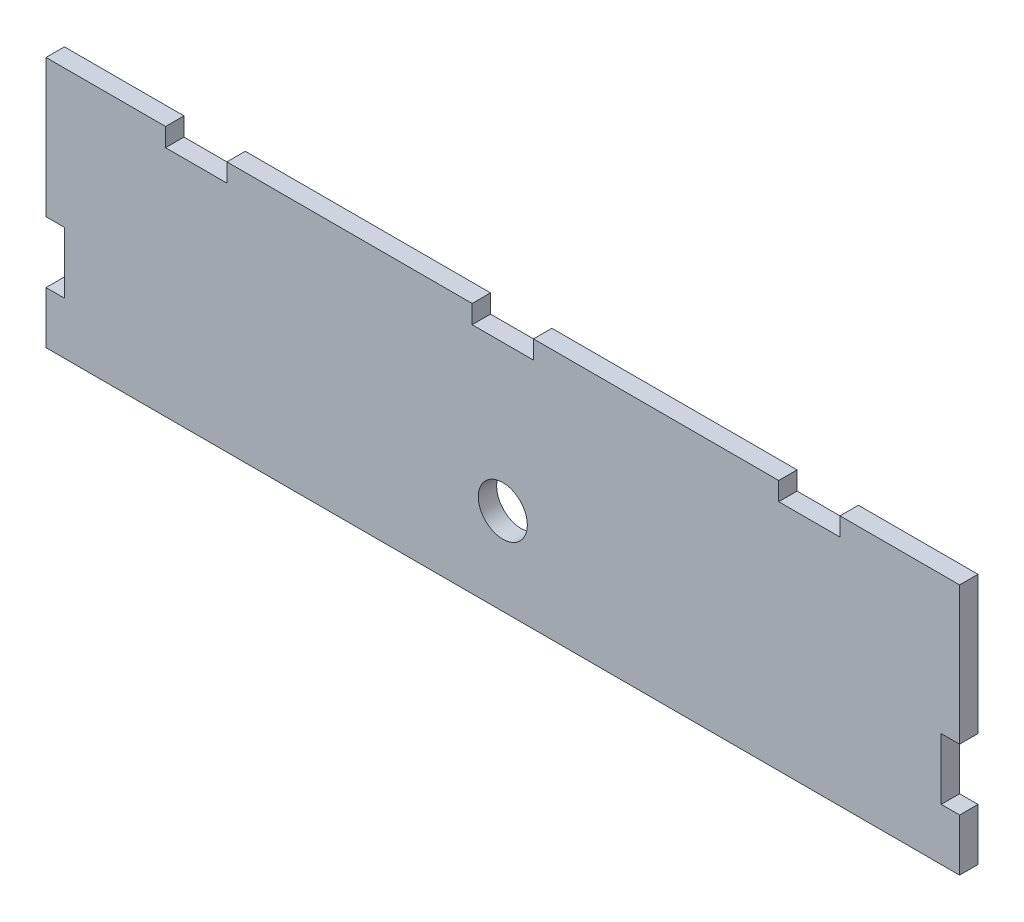
SolidWorks part; units mm, degrees
ref_plane "Front Plane" through (0, 0, 0) normal (0, 0, 1) x (1, 0, 0)
ref_plane "Top Plane" through (0, 0, 0) normal (0, 1, 0) x (1, 0, 0)
ref_plane "Right Plane" through (0, 0, 0) normal (1, 0, 0) x (0, 0, -1)
sketch "Sketch1" plane through (0, 0, 0) normal (0, 0, 1) x (1, 0, 0)
  line L2 (-74.5, 14) -> (-74.5, -8.5)
  line L3 (-74.5, -27) -> (74.5, -27)
  line L4 (74.5, 14) -> (74.5, -8.5)
  line L7 (-5, 14) -> (-5, 11)
  line L8 (-5, 11) -> (5, 11)
  line L9 (5, 14) -> (5, 11)
  line L11 (45, 14) -> (45, 11)
  line L12 (45, 11) -> (55, 11)
  line L13 (55, 14) -> (55, 11)
  line L27 (71.5, -8.5) -> (74.5, -8.5)
  line L28 (71.5, -8.5) -> (71.5, -18.5)
  line L29 (71.5, -18.5) -> (74.5, -18.5)
  line L31 (-71.5, -18.5) -> (-74.5, -18.5)
  line L32 (-71.5, -8.5) -> (-71.5, -18.5)
  line L33 (-71.5, -8.5) -> (-74.5, -8.5)
  line L34 (-74.5, -18.5) -> (-74.5, -27)
  line L35 (74.5, -18.5) -> (74.5, -27)
  line L37 (-55, 14) -> (-55, 11)
  line L38 (-45, 11) -> (-55, 11)
  line L39 (-45, 14) -> (-45, 11)
  line L41 (74.5, 14) -> (55, 14)
  line L42 (-55, 14) -> (-74.5, 14)
  line L43 (-5, 14) -> (-45, 14)
  line L44 (45, 14) -> (5, 14)
  dimension "D1" = 3
  dimension "D2" = 149
  dimension "D3" = 3
  dimension "D4" = 41
  dimension "D5" = 10
  dimension "D7" = 3
  dimension "D8" = 10
  dimension "D9" = 8.5
  dimension "D6" = 40
extrude "Boss-Extrude1" add sketch "Sketch1" along normal blind 3
sketch "Sketch2" plane through (0, 0, 0) normal (0, 0, 1) x (1, 0, 0)
  line L0 (-74.5, -27) -> (74.5, -27) construction
  line L1 (0, -1.65) -> (0, 1.65) construction
  circle A0 centre (0, -12.79) radius 4
  point P4 (0, 0)
  dimension "D1" = 8
  dimension "D2" = 14.21
extrude "Cut-Extrude1" cut sketch "Sketch2" along normal through all
